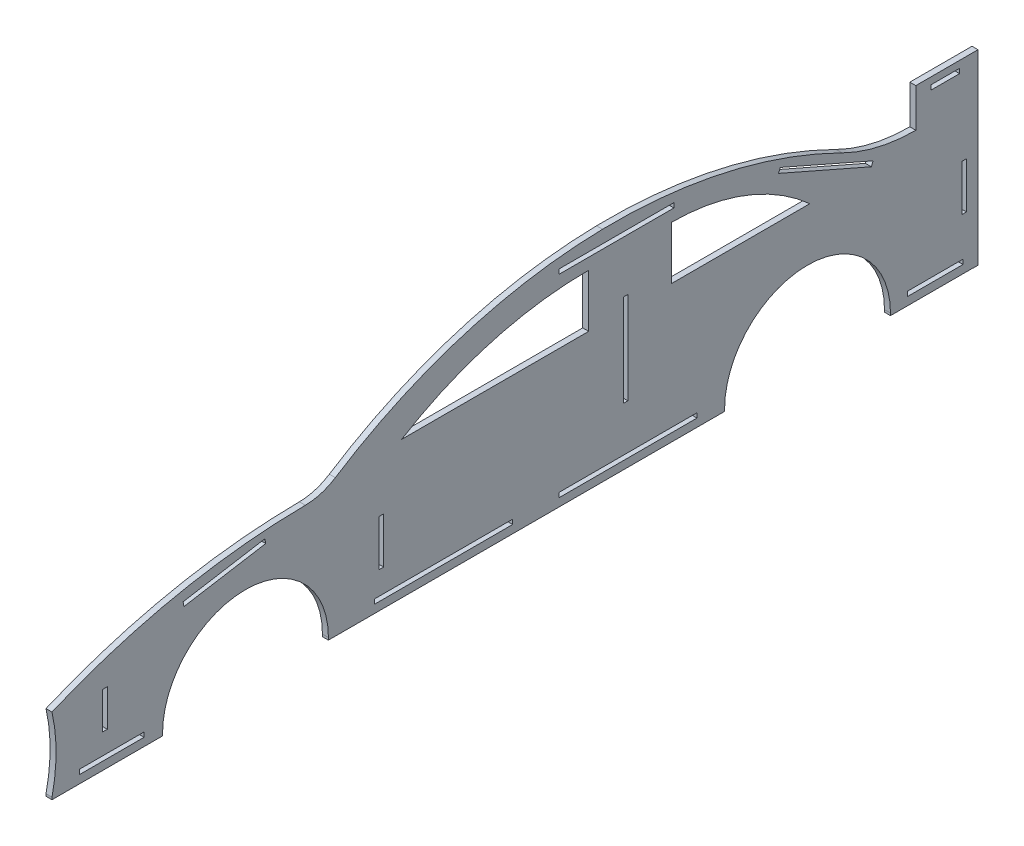
SolidWorks part; units mm, degrees
ref_plane "Front Plane" through (0, 0, 0) normal (0, 0, 1) x (1, 0, 0)
ref_plane "Top Plane" through (0, 0, 0) normal (0, 1, 0) x (1, 0, 0)
ref_plane "Right Plane" through (0, 0, 0) normal (1, 0, 0) x (0, 0, -1)
sketch "Sketch1" plane through (0, 0, 0) normal (1, 0, 0) x (0, 0, -1)
  line L1 (-118.6325, 0) -> (81.3675, 0) construction
  line L2 (81.3675, 0) -> (81.3675, 40)
  line L3 (81.3675, 40) -> (68.8675, 40)
  line L4 (68.8675, 40) -> (68.8675, 31.6)
  line L5 (55, 0) -> (-55, 0) construction
  line L6 (-42.7325, 29.3048) -> (-2.1325, 29.3048)
  line L7 (-2.1325, 29.3048) -> (-2.1325, 40.8048)
  line L8 (81.3675, 0) -> (63.3675, 0)
  line L9 (27.3675, 0) -> (-58.6325, 0)
  line L10 (-94.6325, 0) -> (-118.6325, 0)
  arc A0 (68.8675, 31.6) -> (52.8675, 35.3504) centre (68.8675, 67.6046) cw
  arc A1 (52.8675, 35.3504) -> (0.8675, 47) centre (3.0756, -65.0245) ccw
  arc A2 (0.8675, 47) -> (-57.1325, 29.3048) centre (3.0569, -64.0776) ccw
  arc A3 (-57.1325, 29.3048) -> (-63.6325, 27.3629) centre (-63.7309, 39.542) cw
  arc A4 (-63.6325, 27.3629) -> (-118.6325, 16) centre (-62.4659, -117.0737) ccw
  arc A5 (-118.6325, 16) -> (-118.6325, 0) centre (-154.0124, 8) cw
  arc A6 (-2.1325, 40.8048) -> (-42.7325, 29.3048) centre (-2.1325, -36.6131) ccw
  arc A7 (-94.6325, 0) -> (-58.6325, 0) centre (-76.6325, 0) cw
  arc A8 (63.3675, 0) -> (27.3675, 0) centre (45.3675, 0) ccw
  dimension "D1" = 200
  dimension "D7" = 18
  dimension "D2" = 40
  dimension "D3" = 16
  dimension "D4" = 86
  dimension "D5" = 0
  dimension "D6" = 55
  dimension "D8" = 6.5
  dimension "D9" = 58
  dimension "D10" = 52
  dimension "D11" = 16
  dimension "D12" = 12.5
  dimension "D13" = 18
  dimension "D14" = 47
  dimension "D15" = 8.4
  dimension "D16" = 24
  dimension "D17" = 11.5
  dimension "D18" = 40.6
extrude "Boss-Extrude1" add sketch "Sketch1" along normal blind 1.3
sketch "Sketch2" plane through (1.3, 0, 0) normal (1, 0, 0) x (0, 0, -1)
  line L0 (81.3675, 40) -> (68.8675, 40) construction
  line L1 (72.1175, 38.5) -> (78.3675, 38.5)
  line L2 (72.1175, 38.5) -> (72.1175, 37.5)
  line L3 (72.1175, 37.5) -> (78.3675, 37.5)
  line L4 (78.3675, 38.5) -> (78.3675, 37.5)
  line L5 (72.1175, 38.5) -> (78.3675, 37.5) construction
  line L6 (72.1175, 37.5) -> (78.3675, 38.5) construction
  line L7 (81.3675, 0) -> (81.3675, 40) construction
  point P0 (75.2425, 38)
  dimension "D1" = 1
  dimension "D2" = 6.25
  dimension "D3" = 1.5
  dimension "D4" = 3
extrude "Cut-Extrude1" cut sketch "Sketch2" against normal through all
sketch "Sketch3" plane through (1.3, 0, 0) normal (1, 0, 0) x (0, 0, -1)
  line L0 (55, 0) -> (-55, 0) construction
  line L1 (67.1175, 2.25) -> (79.1175, 2.25)
  line L2 (67.1175, 2.25) -> (67.1175, 1.25)
  line L3 (67.1175, 1.25) -> (79.1175, 1.25)
  line L4 (79.1175, 2.25) -> (79.1175, 1.25)
  line L5 (67.1175, 2.25) -> (79.1175, 1.25) construction
  line L6 (67.1175, 1.25) -> (79.1175, 2.25) construction
  line L7 (81.3675, 0) -> (81.3675, 40) construction
  line L8 (-90, 21.5) -> (-47.3332, 21.5) construction
  line L9 (-8.6325, 2.25) -> (21.3675, 2.25)
  line L10 (-8.6325, 2.25) -> (-8.6325, 1.25)
  line L11 (-8.6325, 1.25) -> (21.3675, 1.25)
  line L12 (21.3675, 2.25) -> (21.3675, 1.25)
  line L13 (-8.6325, 2.25) -> (21.3675, 1.25) construction
  line L14 (-8.6325, 1.25) -> (21.3675, 2.25) construction
  line L15 (-112.6325, 2.25) -> (-98.6325, 2.25)
  line L16 (-112.6325, 2.25) -> (-112.6325, 1.25)
  line L17 (-112.6325, 1.25) -> (-98.6325, 1.25)
  line L18 (-98.6325, 2.25) -> (-98.6325, 1.25)
  line L19 (-112.6325, 2.25) -> (-98.6325, 1.25) construction
  line L20 (-112.6325, 1.25) -> (-98.6325, 2.25) construction
  line L21 (-90.165, 22.4863) -> (-72.4119, 25.4571)
  line L22 (-72.4119, 25.4571) -> (-72.2469, 24.4709)
  line L23 (-72.2469, 24.4709) -> (-90, 21.5)
  line L24 (-90, 21.5) -> (-90.165, 22.4863)
  line L25 (47.3092, 35.8764) -> (20.0904, 47.8087) construction
  line L26 (-107.6325, 14.75) -> (-106.6325, 14.75)
  line L27 (-107.6325, 14.75) -> (-107.6325, 6.75)
  line L28 (-107.6325, 6.75) -> (-106.6325, 6.75)
  line L29 (-106.6325, 14.75) -> (-106.6325, 6.75)
  line L30 (-107.6325, 14.75) -> (-106.6325, 6.75) construction
  line L31 (-107.6325, 6.75) -> (-106.6325, 14.75) construction
  line L32 (39.459, 39.3178) -> (59.6078, 30.4848)
  line L33 (59.6078, 30.4848) -> (59.2063, 29.5689)
  line L34 (59.2063, 29.5689) -> (39.0575, 38.4019)
  line L35 (39.0575, 38.4019) -> (39.459, 39.3178)
  line L36 (0, 55) -> (0, -55) construction
  line L37 (-48.6325, 2.25) -> (-18.6325, 2.25)
  line L38 (-48.6325, 2.25) -> (-48.6325, 1.25)
  line L39 (-48.6325, 1.25) -> (-18.6325, 1.25)
  line L40 (-18.6325, 2.25) -> (-18.6325, 1.25)
  line L41 (-48.6325, 2.25) -> (-18.6325, 1.25) construction
  line L42 (-48.6325, 1.25) -> (-18.6325, 2.25) construction
  line L43 (-72.4119, 25.4571) -> (-90.165, 22.4863) construction
  line L44 (-72.2469, 24.4709) -> (-90.1518, 21.4746) construction
  line L45 (-76.6325, 6.75) -> (-76.6325, 0) construction
  line L46 (-113.8359, 18.5251) -> (-113.6709, 17.5389) construction
  line L47 (-52.6862, 28.7581) -> (-52.5211, 27.7718) construction
  circle A0 centre (-76.6325, 6.75) radius 15 construction
  point P0 (73.1175, 1.75)
  point P9 (6.3675, 1.75)
  point P14 (-105.6325, 1.75)
  point P29 (-107.1325, 10.75)
  point P34 (-107.1325, 6.75)
  point P35 (-33.6325, 1.75)
  point P44 (21.3675, 1.75)
  dimension "D30" = 24
  dimension "D1" = 1
  dimension "D2" = 12
  dimension "D3" = 1.25
  dimension "D4" = 2.25
  dimension "D5" = 1
  dimension "D6" = 30
  dimension "D7" = 1.25
  dimension "D8" = 1
  dimension "D9" = 1.25
  dimension "D10" = 14
  dimension "D11" = 18
  dimension "D12" = 1
  dimension "D13" = 9.5
  dimension "D14" = 1
  dimension "D15" = 8
  dimension "D16" = 6.75
  dimension "D17" = 188
  dimension "D18" = 1
  dimension "D19" = 22
  dimension "D20" = 1.75
  dimension "D21" = 60
  dimension "D22" = 180
  dimension "D23" = 1
  dimension "D24" = 30
  dimension "D25" = 10
  dimension "D26" = 1.25
  dimension "D27" = 21.5
  dimension "D28" = 90
  dimension "D29" = 6.75
  dimension "D31" = 20
extrude "Cut-Extrude2" cut sketch "Sketch3" against normal through all
sketch "Sketch4" plane through (1.3, 0, 0) normal (1, 0, 0) x (0, 0, -1)
  line L0 (81.3675, 0) -> (81.3675, 40) construction
  line L1 (78.8675, 20.75) -> (79.8675, 20.75)
  line L2 (78.8675, 20.75) -> (78.8675, 10.75)
  line L3 (78.8675, 10.75) -> (79.8675, 10.75)
  line L4 (79.8675, 20.75) -> (79.8675, 10.75)
  line L5 (79.1175, 2.25) -> (67.1175, 2.25) construction
  point P6 (79.3675, 10.75)
  dimension "D1" = 1
  dimension "D2" = 1.5
  dimension "D3" = 10
  dimension "D4" = 8.5
extrude "Cut-Extrude3" cut sketch "Sketch4" against normal through all
sketch "Sketch5" plane through (1.3, 0, 0) normal (1, 0, 0) x (0, 0, -1)
  line L0 (55, 0) -> (-55, 0) construction
  line L1 (-8.6325, 44.25) -> (16.3675, 44.25)
  line L2 (-8.6325, 44.25) -> (-8.6325, 43.25)
  line L3 (-8.6325, 43.25) -> (16.3675, 43.25)
  line L4 (16.3675, 44.25) -> (16.3675, 43.25)
  line L5 (5.3675, 32) -> (6.3675, 32)
  line L6 (5.3675, 32) -> (5.3675, 12)
  line L7 (5.3675, 12) -> (6.3675, 12)
  line L8 (6.3675, 32) -> (6.3675, 12)
  line L11 (81.3675, 0) -> (81.3675, 40) construction
  dimension "D1" = 1
  dimension "D2" = 25
  dimension "D3" = 43.25
  dimension "D4" = 1
  dimension "D5" = 20
  dimension "D6" = 75
  dimension "D7" = 12
  dimension "D8" = 10
extrude "Cut-Extrude4" cut sketch "Sketch5" against normal through all
sketch "Sketch6" plane through (1.3, 0, 0) normal (1, 0, 0) x (0, 0, -1)
  line L0 (-18.6325, 2.25) -> (-48.6325, 2.25) construction
  line L1 (-47.6325, 17.25) -> (-46.6325, 17.25)
  line L2 (-47.6325, 17.25) -> (-47.6325, 7.25)
  line L3 (-47.6325, 7.25) -> (-46.6325, 7.25)
  line L4 (-46.6325, 17.25) -> (-46.6325, 7.25)
  line L5 (81.3675, 0) -> (81.3675, 40) construction
  dimension "D1" = 1
  dimension "D2" = 10
  dimension "D3" = 5
  dimension "D4" = 128
extrude "Cut-Extrude5" cut sketch "Sketch6" against normal through all
sketch "Sketch7" plane through (0, 0, 0) normal (1, 0, 0) x (0, 0, -1)
  line L0 (55, 0) -> (-55, 0) construction
  line L1 (-118.6325, 0) -> (-94.6325, 0)
  line L2 (-118.6325, 0) -> (-118.6325, -0.5)
  line L3 (-118.6325, -0.5) -> (-94.6325, -0.5)
  line L4 (-94.6325, 0) -> (-94.6325, -0.5)
  line L6 (-58.6325, 0) -> (27.3675, 0)
  line L7 (-58.6325, 0) -> (-58.6325, -0.5)
  line L8 (-58.6325, -0.5) -> (27.3675, -0.5)
  line L9 (27.3675, 0) -> (27.3675, -0.5)
  line L10 (63.3675, 0) -> (81.3675, 0)
  line L11 (63.3675, 0) -> (63.3675, -0.5)
  line L12 (63.3675, -0.5) -> (81.3675, -0.5)
  line L13 (81.3675, 0) -> (81.3675, -0.5)
  arc A0 (-118.6325, 0) -> (-118.6325, 16) centre (-154.0124, 8) ccw construction
  arc A1 (-58.6325, 0) -> (-94.6325, 0) centre (-76.6325, 0) ccw construction
  arc A2 (63.3675, 0) -> (27.3675, 0) centre (45.3675, 0) ccw construction
  dimension "D1" = 0.5
  dimension "D2" = 18
  dimension "D3" = 0.5
  dimension "D4" = 86
  dimension "D5" = 0.5
  dimension "D6" = 24
extrude "Boss-Extrude2" add sketch "Sketch7" along normal blind 1.3
sketch "Sketch8" plane through (1.3, 0, 0) normal (1, 0, 0) x (0, 0, -1)
  line L0 (-76.6325, 6.75) -> (-76.6325, 0) construction
  line L2 (45.3675, 6.75) -> (45.3675, 0) construction
  circle A0 centre (-76.6325, 6.75) radius 15
  circle A1 centre (45.3675, 6.75) radius 15
  dimension "D2" = 30
  dimension "D4" = 30
  dimension "D1" = 6.75
  dimension "D3" = 6.75
ref_plane "Plane1" through (0, 0, 15.63) normal (0, 0, 1) x (1, 0, 0)
sketch "Sketch9" plane through (1.3, 0, 0) normal (1, 0, 0) x (0, 0, -1)
  line L0 (-42.7325, 29.3048) -> (55.8266, 29.3048) construction
  line L1 (-2.1325, 40.8048) -> (35.3297, 40.8048) construction
  line L2 (15.8675, 40.8048) -> (15.8675, 29.3048)
  line L3 (15.8675, 29.3048) -> (45.8675, 29.3048)
  line L4 (-2.1325, 29.3048) -> (-2.1325, 40.8048) construction
  arc A0 (15.8675, 40.8048) -> (45.8675, 29.3048) centre (15.8675, -4.0757) cw
  dimension "D1" = 30
  dimension "D2" = 18
extrude "Cut-Extrude6" cut sketch "Sketch9" against normal through all
sketch "Sketch10" plane through (0, 0, 0) normal (1, 0, 0) x (0, 0, -1)
  line L1 (81.3675, 40) -> (82.3675, 40)
  line L2 (81.3675, 40) -> (81.3675, -0.5307)
  line L3 (81.3675, -0.5307) -> (82.3675, -0.5307)
  line L4 (82.3675, 40) -> (82.3675, -0.5307)
  dimension "D1" = 1
extrude "Boss-Extrude3" add sketch "Sketch10" along normal blind 1.3
